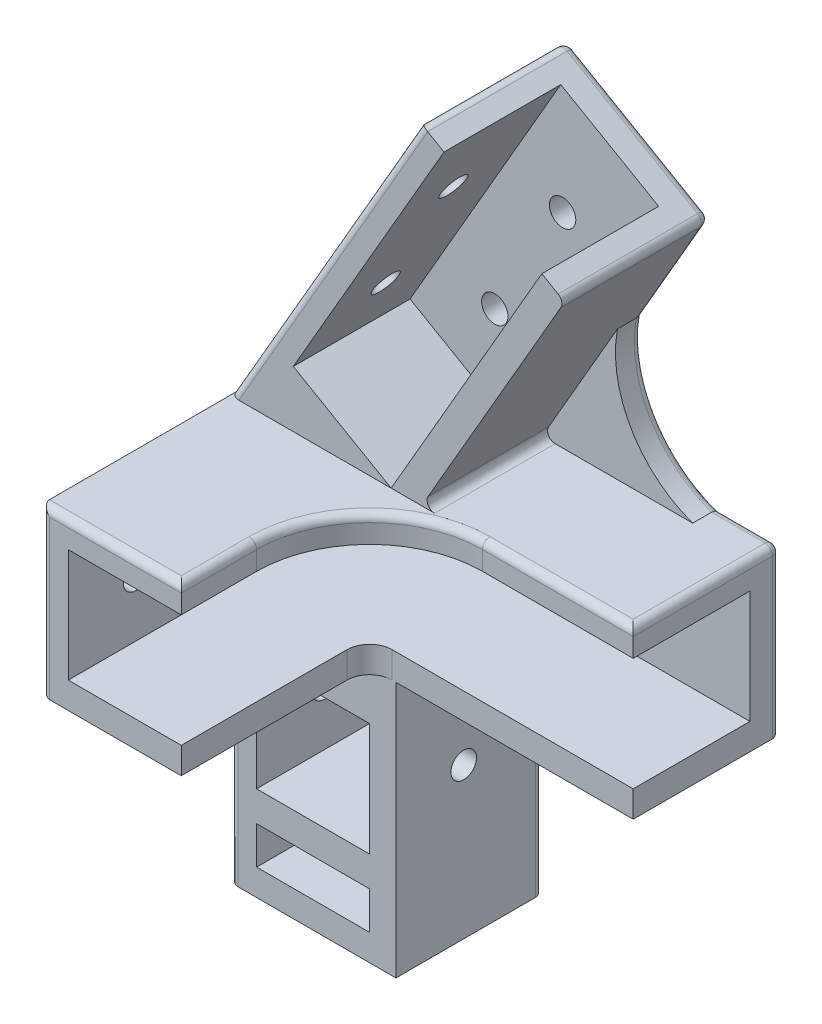
SolidWorks part; units mm, degrees
ref_plane "Front Plane" through (0, 0, 0) normal (0, 0, 1) x (1, 0, 0)
ref_plane "Top Plane" through (0, 0, 0) normal (0, 1, 0) x (1, 0, 0)
ref_plane "Right Plane" through (0, 0, 0) normal (1, 0, 0) x (0, 0, -1)
sketch "Sketch1" plane through (0, 0, 0) normal (0, 0, 1) x (1, 0, 0)
  line L1 (-5.6994, 32.9163) -> (16.3006, 32.9163)
  line L2 (-5.6994, 10.9163) -> (-5.6994, -23.0837)
  line L3 (-5.6994, -23.0837) -> (16.3006, -23.0837)
  line L4 (16.3006, 32.9163) -> (16.3006, -23.0837)
  line L5 (-5.6994, 10.9163) -> (-37.1994, 10.9163)
  line L7 (-5.6994, 32.9163) -> (-37.1994, 32.9163)
  line L8 (-37.1994, 10.9163) -> (-37.1994, 32.9163)
  dimension "D1" = 22
  dimension "D2" = 22
  dimension "D3" = 56
  dimension "D4" = 53.5
extrude "Boss-Extrude1" add sketch "Sketch1" along normal blind 19.5
sketch "Sketch3" plane through (0, 0, 19.5) normal (0, 0, 1) x (1, 0, 0)
  line L1 (16.3006, 32.9163) -> (-2.1994, 32.9163)
  line L2 (16.3006, 32.9163) -> (16.3006, 10.9163)
  line L3 (16.3006, 10.9163) -> (-2.1994, 10.9163)
  line L4 (-2.1994, 32.9163) -> (-2.1994, 10.9163)
  dimension "D1" = 18.5
extrude "Boss-Extrude2" add sketch "Sketch3" along normal blind 25
sketch "Sketch5" plane through (0, 0, 44.5) normal (0, 0, 1) x (1, 0, 0)
  line L0 (-37.1994, 32.9163) -> (-37.1994, 10.9163) construction
  line L1 (-37.1994, 29.4163) -> (12.8006, 29.4163)
  line L2 (-37.1994, 29.4163) -> (-37.1994, 14.4163)
  line L3 (-37.1994, 14.4163) -> (12.8006, 14.4163)
  line L4 (12.8006, 29.4163) -> (12.8006, 14.4163)
  line L5 (16.3006, 10.9163) -> (16.3006, 32.9163) construction
  line L6 (-2.1994, 4.4163) -> (12.8006, 4.4163)
  line L7 (-2.1994, 4.4163) -> (-2.1994, -10.5837)
  line L8 (-2.1994, -10.5837) -> (12.8006, -10.5837)
  line L9 (12.8006, 4.4163) -> (12.8006, -10.5837)
  line L12 (-2.1994, 32.9163) -> (-37.1994, 32.9163) construction
  line L13 (-2.1994, 10.9163) -> (16.3006, 10.9163) construction
  line L15 (16.3006, -23.0837) -> (16.3006, 10.9163) construction
  line L16 (-5.6994, -23.0837) -> (16.3006, -23.0837) construction
  line L17 (-2.1994, -14.5837) -> (12.8006, -14.5837)
  line L18 (-2.1994, -14.5837) -> (-2.1994, -19.5837)
  line L19 (-2.1994, -19.5837) -> (12.8006, -19.5837)
  line L20 (12.8006, -14.5837) -> (12.8006, -19.5837)
  dimension "D1" = 3.5
  dimension "D2" = 6.5
  dimension "D3" = 15
  dimension "D4" = 3.5
  dimension "D5" = 15
  dimension "D6" = 15
  dimension "D7" = 3.5
  dimension "D8" = 15
  dimension "D9" = 4
  dimension "D10" = 3.5
extrude "Cut-Extrude1" cut sketch "Sketch5" against normal offset from surface (40.5 mm away) 4 up to face at (-8.8661, 6.9163, 0)
sketch "Sketch7" plane through (16.3006, 0, 0) normal (1, 0, 0) x (0, 0, -1)
  line L0 (-34.5, 10.9163) -> (-19.5, 10.9163)
  line L1 (-44.5, 10.9163) -> (-19.5, 10.9163) construction
  line L2 (-19.5, 10.9163) -> (-19.5, -4.0837)
  line L3 (-19.5, -23.0837) -> (-19.5, 10.9163) construction
  arc A0 (-34.5, 10.9163) -> (-19.5, -4.0837) centre (-34.5, -4.0837) cw
  dimension "D1" = 15
extrude "Boss-Extrude4" add sketch "Sketch7" against normal blind 3.5
sketch "Sketch8" plane through (0, 0, 0) normal (0, 0, -1) x (-1, 0, 0)
  line L0 (5.6994, 10.9163) -> (20.6994, 10.9163)
  line L1 (37.1994, 10.9163) -> (5.6994, 10.9163) construction
  line L2 (5.6994, 10.9163) -> (5.6994, -4.0837)
  line L3 (5.6994, 10.9163) -> (5.6994, -23.0837) construction
  arc A0 (20.6994, 10.9163) -> (5.6994, -4.0837) centre (20.6994, -4.0837) ccw
  dimension "D1" = 15
extrude "Boss-Extrude5" add sketch "Sketch8" against normal blind 3.5
sketch "Sketch9" plane through (0, 32.9163, 0) normal (0, 1, 0) x (1, 0, 0)
  line L0 (-2.1994, -34.5) -> (-2.1994, -19.5)
  line L1 (-2.1994, -44.5) -> (-2.1994, -19.5) construction
  line L2 (-2.1994, -19.5) -> (-17.1994, -19.5)
  line L3 (-2.1994, -19.5) -> (-37.1994, -19.5) construction
  arc A0 (-2.1994, -34.5) -> (-17.1994, -19.5) centre (-17.1994, -34.5) ccw
  dimension "D1" = 15
extrude "Boss-Extrude6" add sketch "Sketch9" against normal blind 3.5
fillet "Fillet3" radius 3 1 edges
sketch "Sketch11" plane through (0, 0, 0) normal (0, 0, -1) x (-1, 0, 0)
  line L0 (1.1994, -23.0837) -> (1.1994, 10.9163) construction
  line L2 (5.6994, -23.0837) -> (-16.3006, -23.0837) construction
  line L5 (5.6994, -4.0837) -> (5.6994, -23.0837) construction
  text T0 "MR.3" font "Century Gothic" height 12
  dimension "D1" = 4.5
extrude "Cut-Extrude3" cut sketch "Sketch11" against normal blind 1
sketch "Sketch12" plane through (0, 0, 0) normal (0, 0, -1) x (-1, 0, 0)
  line L0 (37.1994, 21.9163) -> (-16.3006, 21.9163) construction
  line L1 (37.1994, 32.9163) -> (37.1994, 10.9163) construction
  line L2 (-16.3006, -23.0837) -> (-16.3006, 32.9163) construction
  line L3 (-12.8006, 14.4163) -> (-12.8006, 29.4163) construction
  circle A0 centre (-5.3006, 21.9163) radius 1.7
  circle A1 centre (10.9494, 21.9163) radius 1.7
  circle A2 centre (27.1994, 21.9163) radius 1.7
  dimension "D4" = 3.4
  dimension "D1" = 7.5
  dimension "D2" = 10
  dimension "D3" = 16.25
extrude "Cut-Extrude4" cut sketch "Sketch12" against normal blind 5
sketch "Sketch13" plane through (-5.6994, 0, 0) normal (-1, 0, 0) x (0, 0, 1)
  line L0 (4, 4.4163) -> (19.5, 4.4163) construction
  line L1 (19.5, 10.9163) -> (19.5, -23.0837) construction
  circle A0 centre (10.5, -3.0837) radius 1.7
  dimension "D2" = 9
  dimension "D3" = 3.4
  dimension "D1" = 7.5
extrude "Cut-Extrude5" cut sketch "Sketch13" against normal blind 45
sketch "Sketch14" plane through (16.3006, 0, 0) normal (1, 0, 0) x (0, 0, -1)
  line L0 (-10.5, -3.0837) -> (-10.5, 32.9163) construction
  line L1 (-44.5, 32.9163) -> (0, 32.9163) construction
  line L2 (-44.5, 21.9163) -> (-10.5, 21.9163) construction
  line L3 (-44.5, 10.9163) -> (-44.5, 32.9163) construction
  circle A0 centre (-10.5, 21.9163) radius 1.7
  circle A1 centre (-35.5, 21.9163) radius 1.7
  dimension "D1" = 3.4
  dimension "D2" = 9
extrude "Cut-Extrude6" cut sketch "Sketch14" against normal blind 45
sketch "Sketch15" plane through (0, -23.0837, 0) normal (0, -1, 0) x (1, 0, 0)
  line L0 (16.3006, 9.75) -> (-5.6994, 9.75) construction
  line L1 (16.3006, 19.5) -> (16.3006, 0) construction
  line L2 (-5.6994, 19.5) -> (-5.6994, 0) construction
  line L3 (5.3006, 19.5) -> (5.3006, 0) construction
  line L4 (-5.6994, 19.5) -> (16.3006, 19.5) construction
  line L5 (-5.6994, 0) -> (16.3006, 0) construction
  circle A0 centre (5.3006, 9.75) radius 1.7
  dimension "D1" = 3.4
extrude "Cut-Extrude7" cut sketch "Sketch15" against normal blind 4
mirror "Mirror2" about plane through (16.3006, 32.9163, 19.5) normal (-1, 0, 0) of "Cut-Extrude7", "Cut-Extrude6", "Cut-Extrude5", "Cut-Extrude4", "Fillet3", "Boss-Extrude6", "Boss-Extrude5", "Boss-Extrude4", "Cut-Extrude1", "Boss-Extrude2", "Boss-Extrude1"
sketch "Sketch16" plane through (0, 0, 0) normal (0, 0, -1) x (-1, 0, 0)
  line L0 (-69.8006, 32.9163) -> (37.1994, 32.9163) construction
  line L1 (-16.3006, 32.9163) -> (53.9943, 32.9163)
  line L2 (-16.3006, 32.9163) -> (-16.3006, -24.95)
  line L3 (-16.3006, -24.95) -> (53.9943, -24.95)
  line L4 (53.9943, 32.9163) -> (53.9943, -24.95)
extrude "Cut-Extrude8" cut sketch "Sketch16" against normal blind 72
sketch "Sketch20" plane through (0, 0, 0) normal (0, 0, -1) x (-1, 0, 0)
  line L0 (-22.3006, -23.0837) -> (-22.3006, 16.9163) construction
  line L1 (-16.3006, -23.0837) -> (-38.3006, -23.0837) construction
  line L2 (-16.3006, 32.9163) -> (-16.3006, -23.0837) construction
  text T0 "ALFR3D" font "Murder Of Mayday" height 10
  dimension "D1" = 6
  dimension "D2" = 40
extrude "Cut-Extrude9" [suppressed] cut sketch "Sketch20" against normal blind 1
sketch "Sketch21" plane through (0, 0, 0) normal (0, 0, -1) x (-1, 0, 0)
  line L0 (-16.3006, 32.9163) -> (-41.6514, 76.8252)
  line L1 (-41.6514, 76.8252) -> (-60.704, 65.8252)
  line L2 (-60.704, 65.8252) -> (-41.704, 32.9163)
  line L3 (-69.8006, 32.9163) -> (-16.3006, 32.9163) construction
  line L4 (-41.704, 32.9163) -> (-16.3006, 32.9163)
  dimension "D1" = 22
  dimension "D2" = 60
  dimension "D3" = 38
extrude "Boss-Extrude7" add sketch "Sketch21" against normal up to surface (19.5 mm away) up to face at (57.3006, 31.1663, 19.5)
sketch "Sketch22" plane through (0, 0, 19.5) normal (0, 0, 1) x (1, 0, 0)
  line L0 (44.6825, 75.0752) -> (24.6722, 40.4163)
  line L1 (60.704, 65.8252) -> (41.6514, 76.8252) construction
  line L2 (24.6722, 40.4163) -> (37.6625, 32.9163)
  line L3 (37.6625, 32.9163) -> (57.6729, 67.5752)
  line L4 (57.6729, 67.5752) -> (44.6825, 75.0752)
  line L5 (41.6514, 76.8252) -> (16.3006, 32.9163) construction
  line L7 (16.3006, 32.9163) -> (41.704, 32.9163) construction
  dimension "D1" = 15
  dimension "D2" = 3.5
extrude "Cut-Extrude10" cut sketch "Sketch22" against normal up to surface (15.5 mm away) up to face at (41.8506, 21.9163, 4)
sketch "Sketch23" plane through (0, 0, 0) normal (0, 0, -1) x (-1, 0, 0)
  line L0 (-61.704, 32.9163) -> (-41.704, 32.9163)
  line L1 (-69.8006, 32.9163) -> (-41.704, 32.9163) construction
  line L2 (-41.704, 32.9163) -> (-51.704, 50.2368)
  line L3 (-60.704, 65.8252) -> (-41.704, 32.9163) construction
  arc A0 (-61.704, 32.9163) -> (-51.704, 50.2368) centre (-66.8048, 47.4082) ccw
  dimension "D1" = 20
extrude "Boss-Extrude8" add sketch "Sketch23" against normal blind 3.5
fillet "Fillet4" radius 1 22 edges at (16.3006, 10.9163, 39.5) (16.3006, 6.5229, 23.8934) (61.5506, 10.9163, 0) (42.694, 6.5229, 0) (34.8006, 32.9163, 39.5) (53.4997, 39.7265, 0) (28.976, 54.8707, 0) (16.3006, -13.5837, 19.5) (16.3006, 4.9163, 0) (38.3006, -13.5837, 0) (69.8006, 32.9163, 9.75) (69.8006, 21.9163, 0) (16.3006, 21.9163, 44.5) (39.194, 32.9163, 23.8934) (25.5506, 32.9163, 44.5) (41.6514, 76.8252, 9.75) (51.1777, 71.3252, 0) (60.704, 65.8252, 9.75)
fillet "Fillet5" radius 1 1 edges
sketch "Sketch24" plane through (-2.0277, 1.1707, 0) normal (-0.866, 0.5, 0) x (0, 0, 1)
  line L0 (12, 36.6566) -> (12, 88.887) construction
  line L1 (18.5, 36.6566) -> (1, 36.6566) construction
  line L2 (19.5, 87.3583) -> (19.5, 37.234) construction
  line L3 (1, 87.3583) -> (19.5, 87.3583) construction
  line L4 (19.5, 44.354) -> (1, 44.354) construction
  circle A0 centre (12, 74.8583) radius 1.75
  circle A1 centre (12, 56.854) radius 1.75
  dimension "D2" = 3.5
  dimension "D3" = 12.5
  dimension "D4" = 12.5
  dimension "D1" = 7.5
extrude "Cut-Extrude11" cut sketch "Sketch24" against normal blind 10
sketch "Sketch25" plane through (0, 0, 0) normal (0, 0, -1) x (-1, 0, 0)
  line L0 (-51.1777, 71.3252) -> (-31.1674, 36.6663) construction
  line L1 (-59.838, 66.3252) -> (-42.5175, 76.3252) construction
  line L2 (-24.6722, 40.4163) -> (-37.6625, 32.9163) construction
  line L3 (-27.2743, 51.9233) -> (-30.3054, 50.1733) construction
  circle A0 centre (-44.9277, 60.4999) radius 1.75
  circle A1 centre (-35.9256, 44.9078) radius 1.75
  dimension "D1" = 3.5
  dimension "D2" = 12.5
  dimension "D3" = 1.75
extrude "Cut-Extrude12" cut sketch "Sketch25" against normal blind 10
